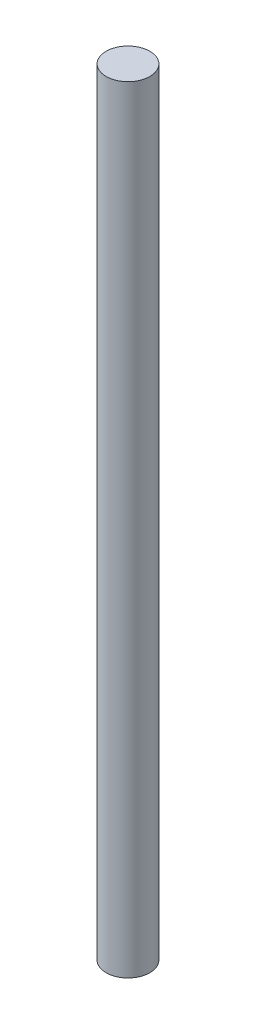
SolidWorks part; units mm, degrees
ref_plane "Plan de face" through (0, 0, 0) normal (0, 0, 1) x (1, 0, 0)
ref_plane "Plan de dessus" through (0, 0, 0) normal (0, 1, 0) x (1, 0, 0)
ref_plane "Plan de droite" through (0, 0, 0) normal (1, 0, 0) x (0, 0, -1)
sketch "Esquisse1" plane through (0, 0, 0) normal (0, 1, 0) x (1, 0, 0)
  circle A0 centre (0, 0) radius 2
  dimension "D1" = 4
extrude "Boss.-Extru.1" add sketch "Esquisse1" along normal blind 71
